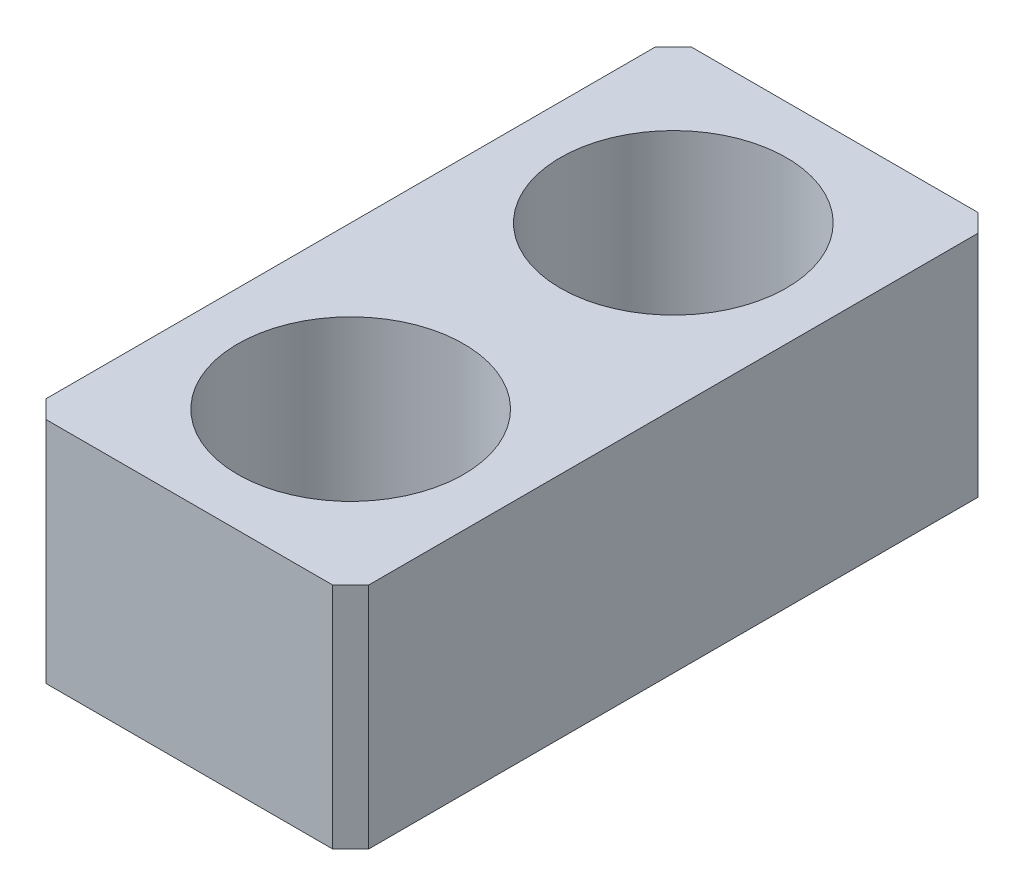
SolidWorks part; units mm, degrees
ref_plane "Спереди" through (0, 0, 0) normal (0, 0, 1) x (1, 0, 0)
ref_plane "Сверху" through (0, 0, 0) normal (0, 1, 0) x (1, 0, 0)
ref_plane "Справа" through (0, 0, 0) normal (1, 0, 0) x (0, 0, -1)
sketch "Эскиз1" plane through (0, 0, 0) normal (0, 1, 0) x (1, 0, 0)
  line L0 (-1.1286, 2.54) -> (1.1286, 2.54)
  line L1 (1.1286, 2.54) -> (1.27, 2.3986)
  line L2 (1.27, 2.3986) -> (1.27, -2.3986)
  line L3 (0, 2.54) -> (0, 0) construction
  line L4 (0, 0) -> (1.27, 0) construction
  line L5 (-1.27, 2.3986) -> (-1.27, -2.3986)
  line L6 (-1.1286, 2.54) -> (-1.27, 2.3986)
  line L7 (1.1286, -2.54) -> (1.27, -2.3986)
  line L8 (-1.1286, -2.54) -> (1.1286, -2.54)
  line L9 (-1.1286, -2.54) -> (-1.27, -2.3986)
  point P14 (-1.27, 0)
  dimension "D1" = 2.54
  dimension "D2" = 1.27
  dimension "D3" = 135
  dimension "D4" = 0.2
extrude "Бобышка-Вытянуть1" add sketch "Эскиз1" along normal blind 1.8
sketch "Эскиз2" plane through (0, 1.8, 0) normal (0, 1, 0) x (1, 0, 0)
  line L0 (0, -1.27) -> (0, 1.27) construction
  circle A0 centre (0, 1.27) radius 0.89
  circle A1 centre (0, -1.27) radius 0.89
  dimension "D1" = 1.78
  dimension "D2" = 2.54
extrude "Вырез-Вытянуть1" cut sketch "Эскиз2" against normal through all
